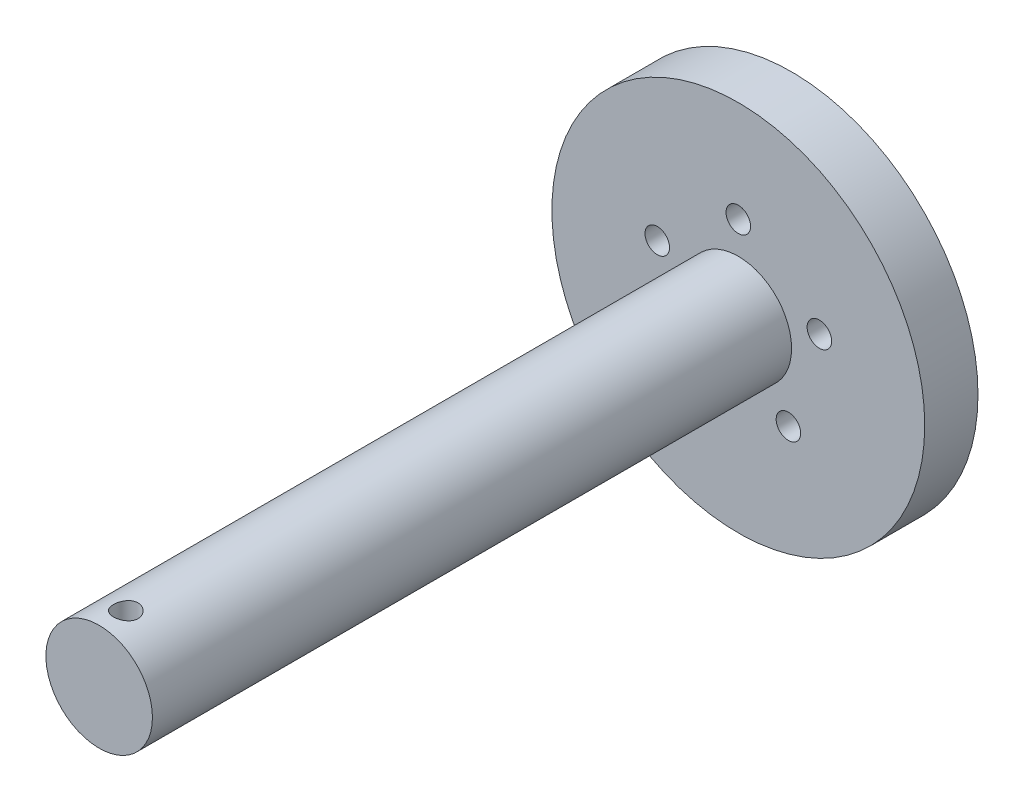
SolidWorks part; units mm, degrees
ref_plane "Front Plane" through (0, 0, 0) normal (0, 0, 1) x (1, 0, 0)
ref_plane "Top Plane" through (0, 0, 0) normal (0, 1, 0) x (1, 0, 0)
ref_plane "Right Plane" through (0, 0, 0) normal (1, 0, 0) x (0, 0, -1)
sketch "Sketch1" plane through (0, 0, 0) normal (0, 0, 1) x (1, 0, 0)
  line L0 (0, 0) -> (0, 20.32) construction
  line L1 (0, 0) -> (19.3255, 6.2792) construction
  line L2 (0, 0) -> (11.9438, -16.4392) construction
  line L3 (0, 0) -> (-11.9438, -16.4392) construction
  line L4 (0, 0) -> (-19.3255, 6.2792) construction
  circle A0 centre (0, 0) radius 44.45
  circle A1 centre (0, 20.32) radius 2.921
  circle A2 centre (19.3255, 6.2792) radius 2.921
  circle A3 centre (11.9438, -16.4392) radius 2.921
  circle A4 centre (-11.9438, -16.4392) radius 2.921
  circle A5 centre (-19.3255, 6.2792) radius 2.921
  point P15 (0, 0)
  dimension "D1" = 88.9
  dimension "D3" = 5.842
  dimension "D2" = 20.32
  dimension "D4" = 5
extrude "Boss-Extrude1" add sketch "Sketch1" along normal blind 12.7
sketch "Sketch2" plane through (0, 0, 12.7) normal (0, 0, 1) x (1, 0, 0)
  circle A0 centre (0, 0) radius 12.7
  dimension "D1" = 25.4
extrude "Boss-Extrude2" add sketch "Sketch2" along normal blind 152.4
sketch "Sketch3" plane through (0, 0, 165.1) normal (0, 0, 1) x (1, 0, 0)
  line L0 (0, 0) -> (0, -12.7) construction
  circle A0 centre (0, 0) radius 12.7 construction
ref_plane "Plane1" through (0, -12.7, 0) normal (0, -1, 0) x (-1, 0, 0)
sketch "Sketch4" plane through (0, -12.7, 0) normal (0, -1, 0) x (-1, 0, 0)
  line L0 (0, -165.1) -> (0, -158.75) construction
  line L1 (-12.7, -165.1) -> (12.7, -165.1) construction
  circle A0 centre (0, -158.75) radius 2.921
  dimension "D2" = 5.842
  dimension "D1" = 6.35
extrude "Cut-Extrude1" cut sketch "Sketch4" against normal up to next
